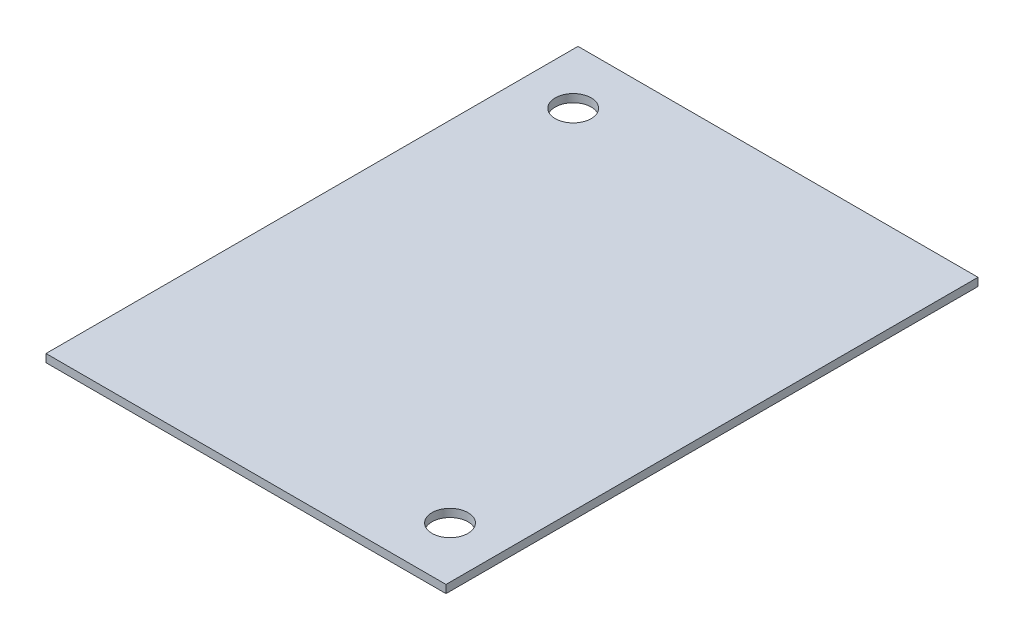
SolidWorks part; units mm, degrees
ref_plane "Front Plane" through (0, 0, 0) normal (0, 0, 1) x (1, 0, 0)
ref_plane "Top Plane" through (0, 0, 0) normal (0, 1, 0) x (1, 0, 0)
ref_plane "Right Plane" through (0, 0, 0) normal (1, 0, 0) x (0, 0, -1)
sketch "Sketch1" plane through (0, 0, 0) normal (0, 1, 0) x (1, 0, 0)
  line L1 (-25, 33.25) -> (25, 33.25)
  line L2 (-25, 33.25) -> (-25, -33.25)
  line L3 (-25, -33.25) -> (25, -33.25)
  line L4 (25, 33.25) -> (25, -33.25)
  line L5 (-25, 33.25) -> (25, -33.25) construction
  line L6 (-25, -33.25) -> (25, 33.25) construction
  circle A0 centre (-18.6, 26.25) radius 2.25
  circle A1 centre (18.6, -26.35) radius 2.25
  point P0 (0, 0)
  point P12 (17.7308, -34.5795)
  dimension "D5" = 4.5
  dimension "D7" = 6.9
  dimension "D8" = 4.5
  dimension "D1" = 50
  dimension "D2" = 66.5
  dimension "D3" = 7
  dimension "D4" = 6.4
  dimension "D6" = 6.4
extrude "Boss-Extrude1" add sketch "Sketch1" along normal blind 1
